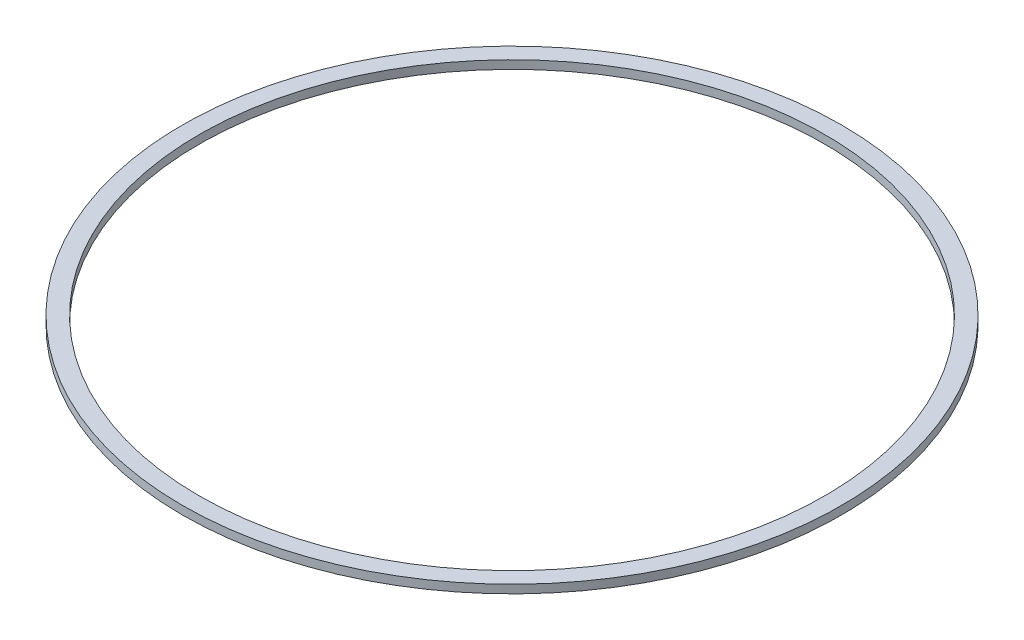
SolidWorks part; units mm, degrees
ref_plane "Front" through (0, 0, 0) normal (0, 0, 1) x (1, 0, 0)
ref_plane "Top" through (0, 0, 0) normal (0, 1, 0) x (1, 0, 0)
ref_plane "Right" through (0, 0, 0) normal (1, 0, 0) x (0, 0, -1)
sketch "Sketch1" plane through (0, 0, 0) normal (0, 1, 0) x (1, 0, 0)
  circle A0 centre (0, 0) radius 250.825
  circle A1 centre (0, 0) radius 238.125
  dimension "D1" = 501.65
  dimension "D2" = 12.7
extrude "Boss-Extrude1" add sketch "Sketch1" along normal blind 6.35
